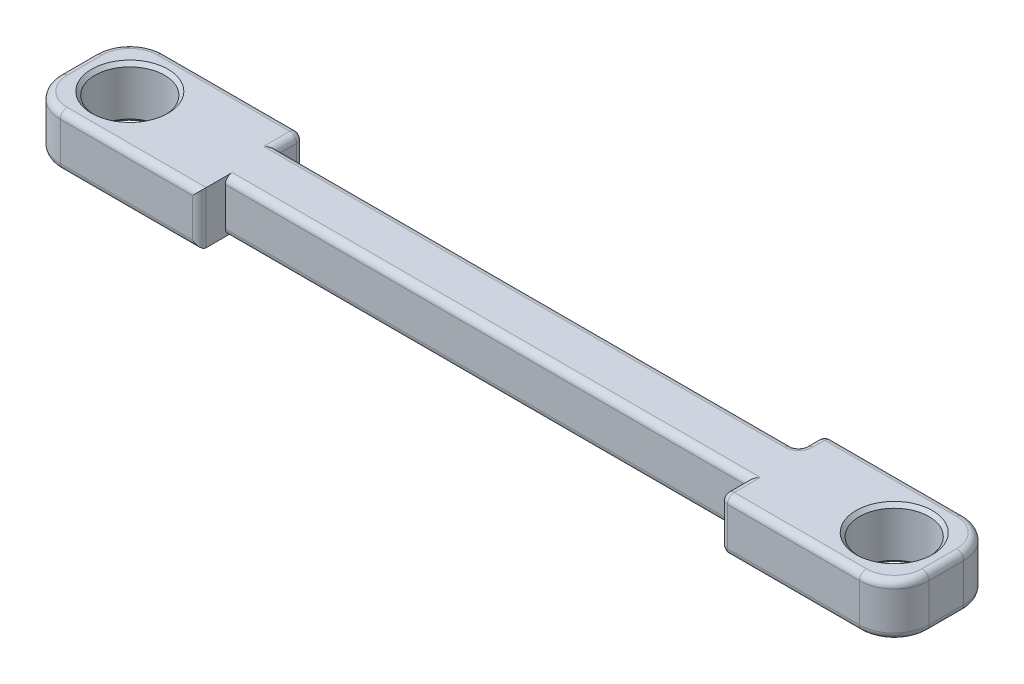
SolidWorks part; units mm, degrees
ref_plane "Front Plane" through (0, 0, 0) normal (0, 0, 1) x (1, 0, 0)
ref_plane "Top Plane" through (0, 0, 0) normal (0, 1, 0) x (1, 0, 0)
ref_plane "Right Plane" through (0, 0, 0) normal (1, 0, 0) x (0, 0, -1)
sketch "Sketch1" plane through (0, 0, 0) normal (0, 1, 0) x (1, 0, 0)
  line L0 (7.5, -1.5) -> (11.5, -1.5)
  line L1 (-11.5, 1.5) -> (0, 1.5)
  line L2 (-12.5, 0.5) -> (-12.5, -0.5)
  line L3 (-11.5, -1.5) -> (0, -1.5)
  line L4 (12.5, 0.5) -> (12.5, -0.5)
  line L5 (-12.5, 1.5) -> (12.5, -1.5) construction
  line L6 (-12.5, -1.5) -> (12.5, 1.5) construction
  line L8 (-7.5, 1.5) -> (-7.5, 0.75)
  line L9 (-7.5, 0.75) -> (7.5, 0.75)
  line L10 (7.5, 1.5) -> (7.5, 0.75)
  line L11 (-7.5, 2.25) -> (7.5, 0.75) construction
  line L12 (-7.5, 0.75) -> (7.5, 2.25) construction
  line L13 (-7.5, -0.75) -> (7.5, -0.75)
  line L14 (-7.5, -0.75) -> (-7.5, -1.5)
  line L16 (7.5, -0.75) -> (7.5, -1.5)
  line L17 (-7.5, -0.75) -> (7.5, -2.25) construction
  line L18 (-7.5, -2.25) -> (7.5, -0.75) construction
  line L19 (7.5, 1.5) -> (11.5, 1.5)
  arc A0 (11.5, -1.5) -> (12.5, -0.5) centre (11.5, -0.5) ccw
  arc A1 (11.5, 1.5) -> (12.5, 0.5) centre (11.5, 0.5) cw
  arc A2 (-11.5, 1.5) -> (-12.5, 0.5) centre (-11.5, 0.5) ccw
  arc A3 (-12.5, -0.5) -> (-11.5, -1.5) centre (-11.5, -0.5) ccw
  point P0 (0, 0)
  point P6 (0, 1.5)
  point P11 (0, -1.5)
  dimension "D7" = 1
  dimension "D1" = 25
  dimension "D2" = 3
  dimension "D3" = 15
  dimension "D4" = 1.5
  dimension "D5" = 15
  dimension "D6" = 1.5
extrude "Boss-Extrude1" add sketch "Sketch1" along normal blind 1.5 contours L19 L10 L9 L8 L1 L2 L3 L14 L13 L16 L0 L4
sketch "Sketch2" plane through (0, 1.5, 0) normal (0, 1, 0) x (1, 0, 0)
  line L0 (-12.5, 0.5) -> (-12.5, -0.5) construction
  line L1 (12.5, 0.5) -> (12.5, -0.5) construction
  circle A0 centre (-11, 0) radius 1
  circle A1 centre (11, 0) radius 1
  point P8 (12.5, 0)
  dimension "D1" = 2
  dimension "D2" = 2
  dimension "D3" = 1.5
  dimension "D4" = 1.5
extrude "Cut-Extrude1" cut sketch "Sketch2" against normal through all
chamfer "Chamfer1" distance 0.1 angle 45 4 edges at (11, 0, 1) (-11, 0, 1) (11, 1.5, 1) (-11, 1.5, 1)
fillet "Fillet1" radius 0.2 34 edges at (7.5, 0, 1.125) (7.5, 0, -1.125) (0, 0, 0.75) (12.5, 1.5, 0) (7.5, 1.5, 1.125) (0, 1.5, 0.75) (-12.5, 1.5, 0) (-7.5, 1.5, -1.125) (7.5, 1.5, -1.125) (-7.5, 0.75, -1.5) (-9.5, 1.5, -1.5) (-9.5, 0, -1.5) (7.5, 0.75, -0.75) (0, 1.5, -0.75) (0, 0, -0.75) (9.5, 1.5, -1.5) (7.5, 0.75, -1.5) (9.5, 0, -1.5) (-9.5, 1.5, 1.5) (-7.5, 0.75, 1.5) (-9.5, 0, 1.5) (7.5, 0.75, 1.5) (9.5, 1.5, 1.5) (9.5, 0, 1.5) (12.2071, 0, -1.2071) (12.5, 0, 0) (12.2071, 0, 1.2071) (12.2071, 1.5, -1.2071) (12.2071, 1.5, 1.2071) (-12.2071, 0, 1.2071) (-12.5, 0, 0) (-12.2071, 0, -1.2071) (-12.2071, 1.5, 1.2071) (-12.2071, 1.5, -1.2071)
